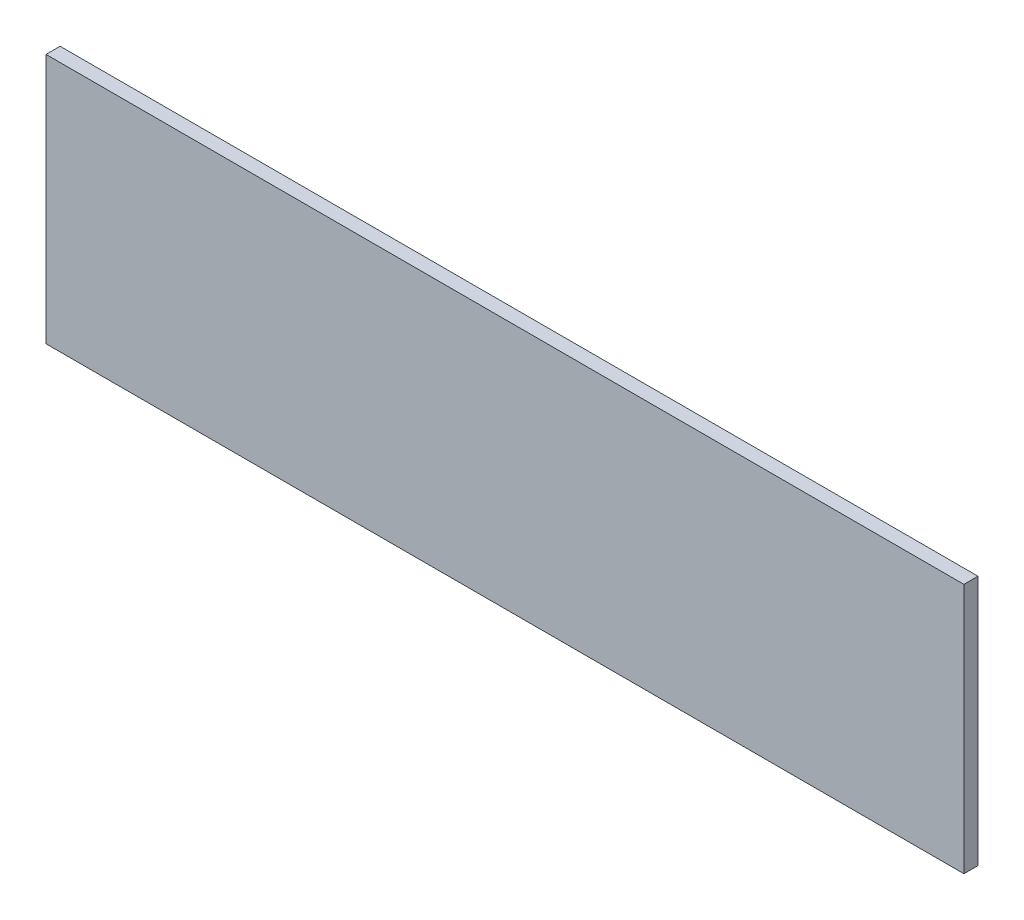
SolidWorks part; units mm, degrees
ref_plane "Front Plane" through (0, 0, 0) normal (0, 0, 1) x (1, 0, 0)
ref_plane "Top Plane" through (0, 0, 0) normal (0, 1, 0) x (1, 0, 0)
ref_plane "Right Plane" through (0, 0, 0) normal (1, 0, 0) x (0, 0, -1)
sketch "Sketch1" plane through (0, 0, 0) normal (0, 0, 1) x (1, 0, 0)
  line L1 (146.5, -40) -> (-146.5, -40)
  line L2 (146.5, -40) -> (146.5, 40)
  line L3 (146.5, 40) -> (-146.5, 40)
  line L4 (-146.5, -40) -> (-146.5, 40)
  line L5 (146.5, -40) -> (-146.5, 40) construction
  line L6 (146.5, 40) -> (-146.5, -40) construction
  point P0 (0, 0)
  dimension "D1" = 293
  dimension "D2" = 80
extrude "Boss-Extrude1" add sketch "Sketch1" along normal blind 4.5
sketch "Sketch2" plane through (0, 0, 4.5) normal (0, 0, 1) x (1, 0, 0)
  line L0 (-146.5, 40) -> (-142, 35.5) construction
  line L1 (-146.5, 40) -> (-142, 40) construction
  line L2 (-146.5, 40) -> (-146.5, 35.5) construction
  line L3 (-146.5, 35.5) -> (-142, 35.5) construction
  line L4 (-142, 40) -> (-142, 35.5) construction
  line L5 (-142, -35.5) -> (-146.5, -40) construction
  line L6 (-146.5, -40) -> (-142, -40) construction
  line L7 (-146.5, -40) -> (-146.5, -35.5) construction
  line L8 (-146.5, -35.5) -> (-142, -35.5) construction
  line L9 (-142, -40) -> (-142, -35.5) construction
  line L10 (142, -35.5) -> (146.5, -40) construction
  line L11 (146.5, -40) -> (142, -40) construction
  line L12 (146.5, -40) -> (146.5, -35.5) construction
  line L13 (146.5, -35.5) -> (142, -35.5) construction
  line L14 (142, -40) -> (142, -35.5) construction
  line L15 (142, 35.5) -> (146.5, 40) construction
  line L16 (146.5, 40) -> (142, 40) construction
  line L17 (146.5, 40) -> (146.5, 35.5) construction
  line L18 (146.5, 35.5) -> (142, 35.5) construction
  line L19 (142, 40) -> (142, 35.5) construction
  circle A0 centre (-144.25, 37.75) radius 1.5
  circle A1 centre (144.25, 37.75) radius 1.5
  circle A2 centre (144.25, -37.75) radius 1.5
  circle A3 centre (-144.25, -37.75) radius 1.5
  circle A4 centre (-144.25, 37.75) radius 3 construction
  dimension "D3" = 4.5
  dimension "D1" = 4.5
  dimension "D2" = 4.5
  dimension "D4" = 4.5
  dimension "D5" = 4.5
  dimension "D6" = 4.5
  dimension "D7" = 4.5
  dimension "D8" = 4.5
extrude "Cut-Extrude1" [suppressed] cut sketch "Sketch2" against normal up to next
